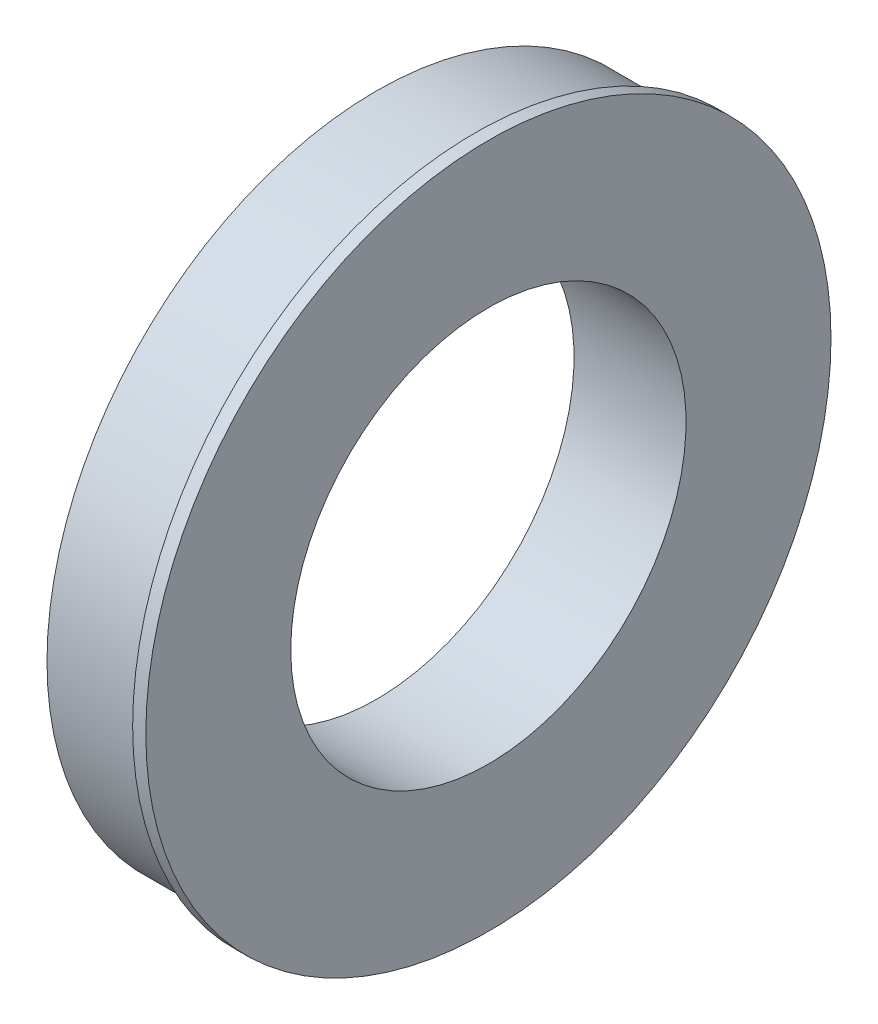
SolidWorks part; units mm, degrees
ref_plane "Front Plane" through (0, 0, 0) normal (0, 0, 1) x (1, 0, 0)
ref_plane "Top Plane" through (0, 0, 0) normal (0, 1, 0) x (1, 0, 0)
ref_plane "Right Plane" through (0, 0, 0) normal (1, 0, 0) x (0, 0, -1)
sketch "Sketch1" plane through (0, 0, 0) normal (1, 0, 0) x (0, 0, -1)
  circle A0 centre (0, 0) radius 38.1
  circle A1 centre (0, 0) radius 63.5
  dimension "D1" = 76.2
  dimension "D2" = 127
extrude "Boss-Extrude1" add sketch "Sketch1" along normal blind 19.05
sketch "Sketch2" plane through (19.05, 0, 0) normal (1, 0, 0) x (0, 0, -1)
  circle A1 centre (0, 0) radius 38.1 construction
  circle A2 centre (0, 0) radius 66.04
  circle A3 centre (0, 0) radius 66.04
  circle A4 centre (0, 0) radius 38.1
  dimension "D1" = 2.54
extrude "Boss-Extrude2" add sketch "Sketch2" along normal blind 2.54
